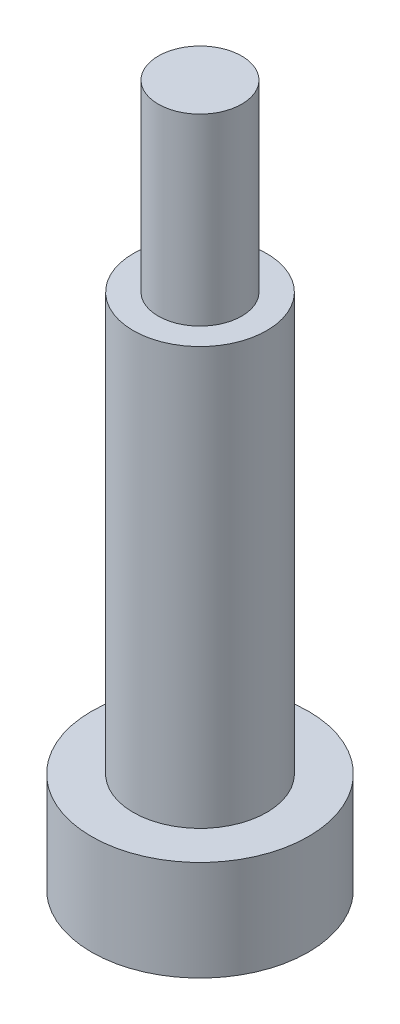
SolidWorks part; units mm, degrees
material "Acero aleado"
ref_plane "Alzado" through (0, 0, 0) normal (0, 0, 1) x (1, 0, 0)
ref_plane "Planta" through (0, 0, 0) normal (0, 1, 0) x (1, 0, 0)
ref_plane "Vista lateral" through (0, 0, 0) normal (1, 0, 0) x (0, 0, -1)
sketch "Croquis1" plane through (0, 0, 0) normal (0, 1, 0) x (1, 0, 0)
  circle A0 centre (152.4, -336.55) radius 2.5
  dimension "D1" = 5
  dimension "D2" = 152.4
  dimension "D3" = 336.55
extrude "Rosca" add sketch "Croquis1" along normal blind 11 from offset 3.175
sketch "Croquis2" plane through (0, 0, 0) normal (0, 1, 0) x (1, 0, 0)
  circle A0 centre (152.4, -336.55) radius 4
  dimension "D1" = 8
  dimension "D2" = 152.4
  dimension "D3" = 336.55
extrude "Hombro" add sketch "Croquis2" along normal blind 25 from offset 28.175
sketch "Croquis3" plane through (0, 0, 0) normal (0, 1, 0) x (1, 0, 0)
  circle A0 centre (152.4, -336.55) radius 6.5
  dimension "D1" = 13
  dimension "D2" = 152.4
  dimension "D3" = 336.55
extrude "Cabeza" add sketch "Croquis3" along normal blind 6 from offset 34.175
sketch "Croquis4" plane through (0, 0, 0) normal (0, 1, 0) x (1, 0, 0)
  circle A0 centre (152.4, -336.55) radius 2.86
  dimension "D1" = 5.72
  dimension "D2" = 152.4
  dimension "D3" = 336.55
extrude "Allen" cut sketch "Croquis4" along normal blind 3.6 from offset 34.175
